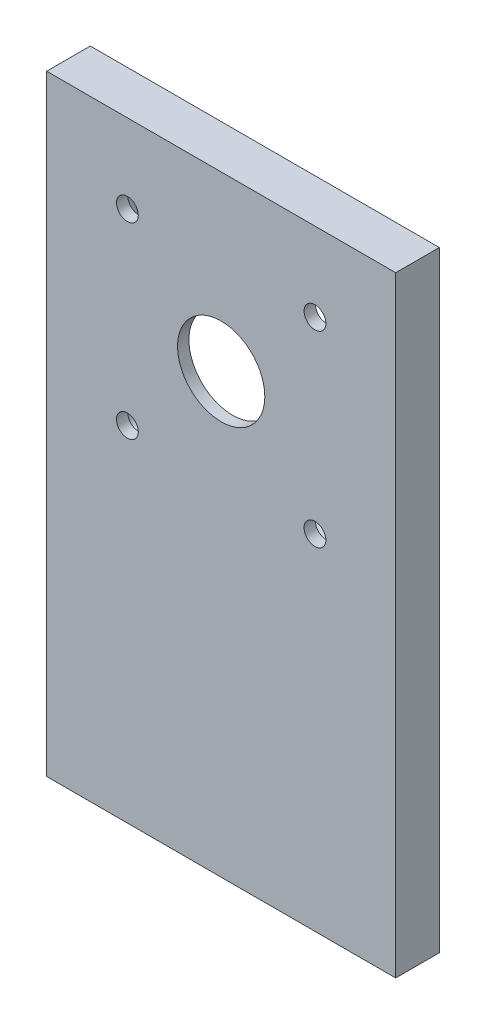
SolidWorks part; units mm, degrees
ref_plane "Front Plane" through (0, 0, 0) normal (0, 0, 1) x (1, 0, 0)
ref_plane "Top Plane" through (0, 0, 0) normal (0, 1, 0) x (1, 0, 0)
ref_plane "Right Plane" through (0, 0, 0) normal (1, 0, 0) x (0, 0, -1)
sketch "Sketch1" plane through (0, 0, 0) normal (0, 0, 1) x (1, 0, 0)
  line L1 (-50.8, -88.9) -> (50.8, -88.9)
  line L2 (-50.8, -88.9) -> (-50.8, 88.9)
  line L3 (-50.8, 88.9) -> (50.8, 88.9)
  line L4 (50.8, -88.9) -> (50.8, 88.9)
  line L5 (-50.8, -88.9) -> (50.8, 88.9) construction
  line L6 (-50.8, 88.9) -> (50.8, -88.9) construction
  point P0 (0, 0)
  dimension "D1" = 101.6
  dimension "D2" = 177.8
extrude "Boss-Extrude1" add sketch "Sketch1" along normal blind 12.7 contours L3 L4 L1 L2
hole_wizard "#10-32 Tapped Hole1" positions "Sketch3" profile "Sketch4" tap size "#10-32" standard "ANSI Inch"
sketch "Sketch3" plane through (0, -88.9, 0) normal (0, -1, 0) x (-1, 0, 0)
  line L0 (50.8, -12.7) -> (50.8, 0) construction
  line L1 (-50.8, -12.7) -> (-50.8, 0) construction
  point P0 (31.75, -6.35)
  point P2 (-31.75, -6.35)
  dimension "D1" = 19.05
  dimension "D2" = 19.05
sketch "Sketch4" plane through (-31.75, -88.9, 6.35) normal (1, 0, 0) x (0, 0, -1)
  line L0 (0, 0) -> (0, 26.6133)
  line L1 (0, 26.6133) -> (2.0193, 25.4)
  line L2 (2.0193, 25.4) -> (2.0193, 0)
  line L5 (2.0193, 0) -> (0, 0)
  line L10 (0, 26.6133) -> (-2.0193, 25.4) construction
  line L11 (0, -6.35) -> (0, 107.95) construction
  dimension "Tap Drill Dia." = 4.0386
  dimension "Tap Drill Depth" = 25.4
  dimension "Drill Angle" = 118
sketch "Sketch5" plane through (0, 0, 12.7) normal (0, 0, 1) x (1, 0, 0)
  line L0 (50.8, -88.9) -> (50.8, 88.9) construction
  circle A0 centre (0, 38.6167) radius 12.7
  circle A1 centre (-27.305, 65.9217) radius 3.175
  circle A2 centre (27.305, 65.9217) radius 3.175
  circle A3 centre (27.305, 11.3117) radius 3.175
  circle A4 centre (-27.305, 11.3117) radius 3.175
  point P12 (-4.9053, 40.5544)
  dimension "D1" = 6.35
  dimension "D2" = 6.35
  dimension "D3" = 6.35
  dimension "D4" = 6.35
  dimension "D13" = 50.8
  dimension "D5" = 27.305
  dimension "D6" = 27.305
  dimension "D7" = 27.305
  dimension "D8" = 27.305
  dimension "D9" = 27.305
  dimension "D10" = 27.305
  dimension "D11" = 27.305
  dimension "D12" = 27.305
extrude "Cut-Extrude1" cut sketch "Sketch5" against normal through all
sketch "Sketch6" plane through (0, 0, 0) normal (0, 0, -1) x (-1, 0, 0)
  line L1 (-30.7975, 7.8192) -> (30.7975, 7.8192)
  line L2 (-30.7975, 7.8192) -> (-30.7975, 69.4142)
  line L3 (-30.7975, 69.4142) -> (30.7975, 69.4142)
  line L4 (30.7975, 7.8192) -> (30.7975, 69.4142)
  line L5 (-30.7975, 7.8192) -> (30.7975, 69.4142) construction
  line L6 (-30.7975, 69.4142) -> (30.7975, 7.8192) construction
  point P0 (0, 38.6167)
  dimension "D1" = 61.595
  dimension "D2" = 61.595
extrude "Cut-Extrude2" cut sketch "Sketch6" against normal blind 9.398
fillet "Fillet1" radius 3.175 4 edges at (-30.7975, 7.8192, 4.699) (30.7975, 7.8192, 4.699) (-30.7975, 69.4142, 4.699) (30.7975, 69.4142, 4.699)
sketch "Sketch7" plane through (0, 0, 0) normal (0, 0, -1) x (-1, 0, 0)
  line L1 (-33.9725, 4.6442) -> (33.9725, 4.6442)
  line L2 (-33.9725, 4.6442) -> (-33.9725, 72.5892)
  line L3 (-33.9725, 72.5892) -> (33.9725, 72.5892)
  line L4 (33.9725, 4.6442) -> (33.9725, 72.5892)
  line L5 (-33.9725, 4.6442) -> (33.9725, 72.5892) construction
  line L6 (-33.9725, 72.5892) -> (33.9725, 4.6442) construction
  point P0 (0, 38.6167)
  dimension "D1" = 67.945
  dimension "D2" = 67.945
extrude "Cut-Extrude3" cut sketch "Sketch7" against normal blind 4.445
fillet "Fillet2" radius 3.175 4 edges at (33.9725, 4.6442, 2.2225) (-33.9725, 4.6442, 2.2225) (-33.9725, 72.5892, 2.2225) (33.9725, 72.5892, 2.2225)
